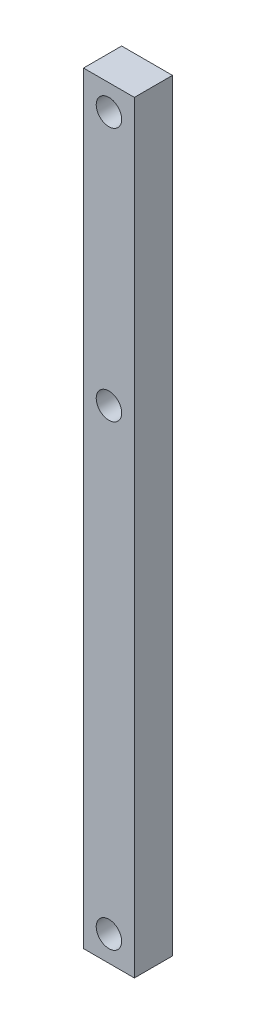
SolidWorks part; units mm, degrees
ref_plane "Front Plane" through (0, 0, 0) normal (0, 0, 1) x (1, 0, 0)
ref_plane "Top Plane" through (0, 0, 0) normal (0, 1, 0) x (1, 0, 0)
ref_plane "Right Plane" through (0, 0, 0) normal (1, 0, 0) x (0, 0, -1)
sketch "Sketch2" plane through (0, 0, 0) normal (0, 0, 1) x (1, 0, 0)
  line L1 (-10, 150) -> (10, 150)
  line L2 (-10, 150) -> (-10, -150)
  line L3 (-10, -150) -> (10, -150)
  line L4 (10, 150) -> (10, -150)
  line L5 (-10, 150) -> (10, -150) construction
  line L6 (-10, -150) -> (10, 150) construction
  point P0 (0, 0)
  dimension "D1" = 300
  dimension "D2" = 20
extrude "Boss-Extrude1" add sketch "Sketch2" along normal blind 15
sketch "Sketch3" plane through (0, 0, 15) normal (0, 0, 1) x (1, 0, 0)
  line L0 (10, 150) -> (-10, 150) construction
  line L1 (-10, -150) -> (10, -150) construction
  circle A0 centre (0, 140) radius 5
  circle A1 centre (0, -140) radius 5
  circle A2 centre (0, 40) radius 5
  dimension "D1" = 10
  dimension "D3" = 100
  dimension "D2" = 10
extrude "Cut-Extrude1" cut sketch "Sketch3" against normal blind 15
